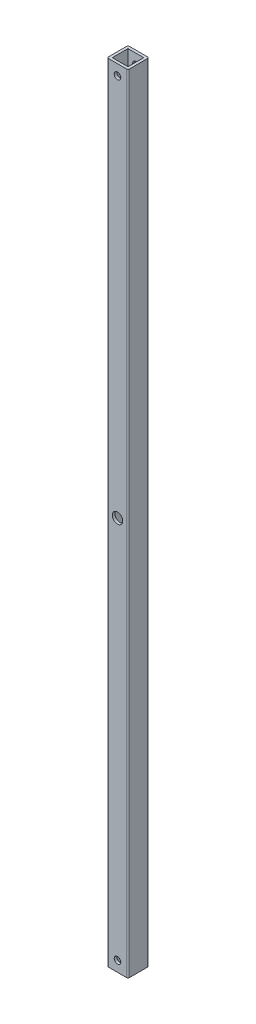
SolidWorks part; units mm, degrees
ref_plane "Front Plane" through (0, 0, 0) normal (0, 0, 1) x (1, 0, 0)
ref_plane "Top Plane" through (0, 0, 0) normal (0, 1, 0) x (1, 0, 0)
ref_plane "Right Plane" through (0, 0, 0) normal (1, 0, 0) x (0, 0, -1)
sketch "Sketch1" plane through (0, 0, 0) normal (0, 1, 0) x (1, 0, 0)
  line L0 (-4.1389, 2.0833) -> (-4.1389, -9.9167)
  line L1 (-6.1389, 4.0833) -> (9.8611, 4.0833)
  line L2 (-6.1389, 4.0833) -> (-6.1389, -11.9167)
  line L3 (-6.1389, -11.9167) -> (9.8611, -11.9167)
  line L4 (9.8611, 4.0833) -> (9.8611, -11.9167)
  line L5 (-4.1389, -9.9167) -> (7.8611, -9.9167)
  line L6 (7.8611, 2.0833) -> (7.8611, -9.9167)
  line L7 (-4.1389, 2.0833) -> (7.8611, 2.0833)
  dimension "D1" = 16
  dimension "D2" = 16
  dimension "D3" = 2
extrude "Boss-Extrude1" add sketch "Sketch1" along normal blind 600
fillet "Fillet1" radius 1 4 edges at (9.8611, 300, -4.0833) (-6.1389, 300, -4.0833) (-6.1389, 300, 11.9167) (9.8611, 300, 11.9167)
sketch "Sketch2" plane through (0, 0, -4.0833) normal (0, 0, -1) x (-1, 0, 0)
  line L0 (-8.8611, 600) -> (5.1389, 600) construction
  line L1 (-9.8611, 0) -> (-9.8611, 600) construction
  line L2 (-8.8611, 0) -> (5.1389, 0) construction
  circle A0 centre (-1.8611, 8) radius 2.5
  circle A1 centre (-1.8611, 592) radius 2.5
  circle A2 centre (-1.8611, 300) radius 4
  point P12 (-1.8611, 0)
  dimension "D1" = 5
  dimension "D4" = 5
  dimension "D8" = 8
  dimension "D2" = 8
  dimension "D3" = 8
  dimension "D5" = 8
  dimension "D6" = 8
  dimension "D7" = 300
  dimension "D9" = 8
extrude "Cut-Extrude1" cut sketch "Sketch2" against normal blind 16
